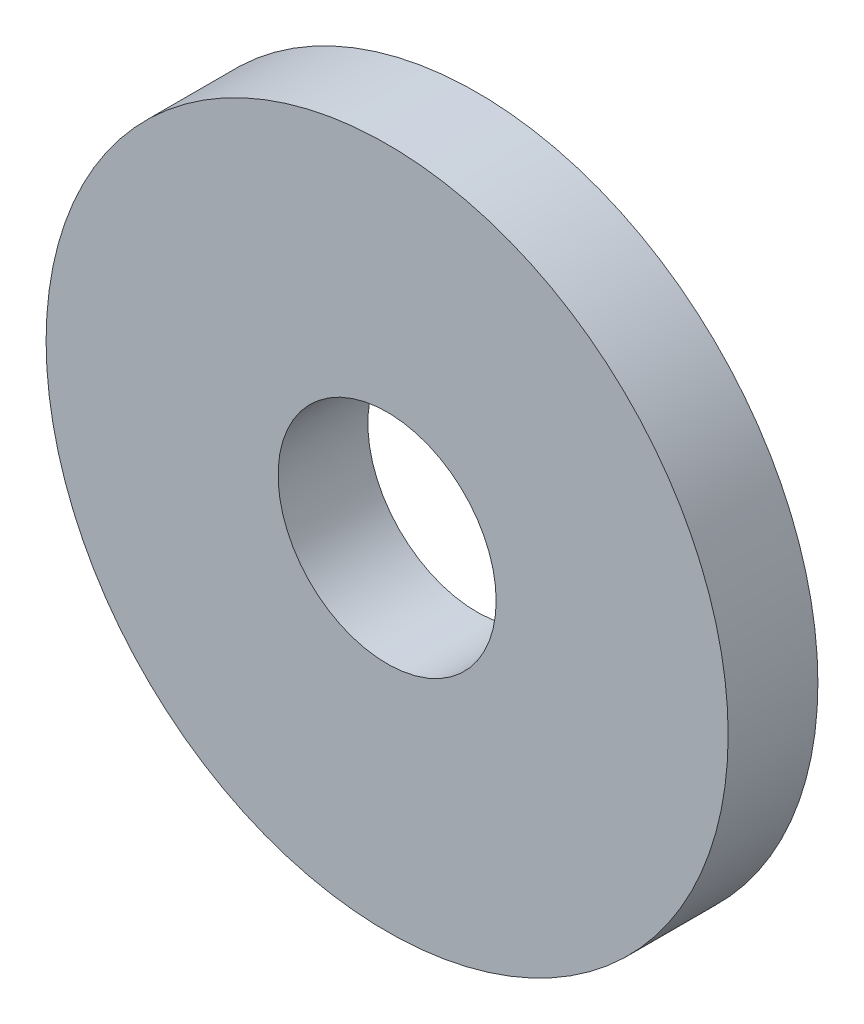
SolidWorks part; units mm, degrees
ref_plane "Ebene vorne" through (0, 0, 0) normal (0, 0, 1) x (1, 0, 0)
ref_plane "Ebene oben" through (0, 0, 0) normal (0, 1, 0) x (1, 0, 0)
ref_plane "Ebene rechts" through (0, 0, 0) normal (1, 0, 0) x (0, 0, -1)
sketch "Skizze1" plane through (0, 0, 0) normal (0, 0, 1) x (1, 0, 0)
  circle A0 centre (0, 0) radius 19
  circle A1 centre (0, 0) radius 6.075
  dimension "D1" = 38
  dimension "D2" = 12.15
extrude "Aufsatz-Linear austragen1" add sketch "Skizze1" along normal blind 5
